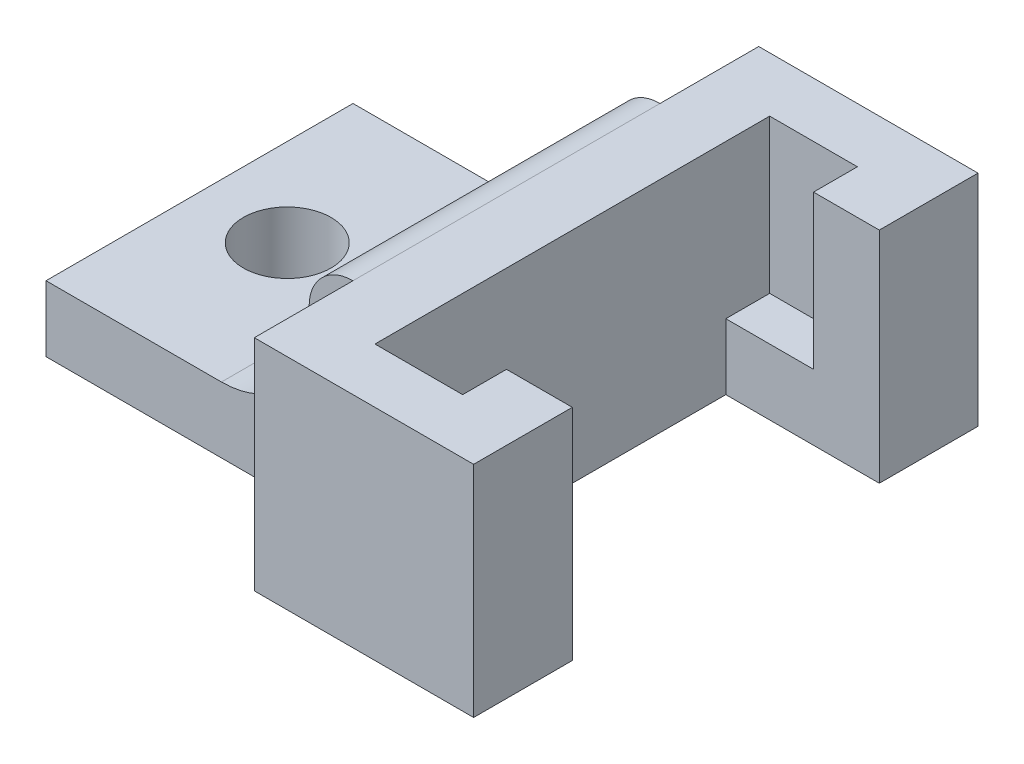
SolidWorks part; units mm, degrees
ref_plane "Front Plane" through (0, 0, 0) normal (0, 0, 1) x (1, 0, 0)
ref_plane "Top Plane" through (0, 0, 0) normal (0, 1, 0) x (1, 0, 0)
ref_plane "Right Plane" through (0, 0, 0) normal (1, 0, 0) x (0, 0, -1)
sketch "Sketch1" plane through (0, 0, 0) normal (0, 1, 0) x (1, 0, 0)
  line L0 (0, 7) -> (14, 7) construction
  line L1 (0, 0) -> (14, 0)
  line L2 (0, 0) -> (0, 14)
  line L3 (0, 14) -> (14, 14)
  line L4 (14, 0) -> (14, 14)
  line L6 (14, 18.5) -> (24, 18.5)
  line L7 (14, 18.5) -> (14, -4.5)
  line L8 (14, -4.5) -> (24, -4.5)
  line L9 (24, 18.5) -> (24, -4.5)
  line L10 (14, 18.5) -> (24, -4.5) construction
  line L11 (14, -4.5) -> (24, 18.5) construction
  line L12 (17, 14) -> (24, 14)
  line L13 (17, 14) -> (17, 0)
  line L14 (17, 0) -> (24, 0)
  line L15 (24, 14) -> (24, 0)
  line L16 (17, 14) -> (24, 0) construction
  line L17 (17, 0) -> (24, 14) construction
  line L18 (17, 16) -> (21, 16) construction
  line L19 (17, 16) -> (17, -2) construction
  line L20 (17, -2) -> (21, -2) construction
  line L21 (21, 16) -> (21, -2) construction
  line L22 (17, 16) -> (21, -2) construction
  line L23 (17, -2) -> (21, 16) construction
  circle A0 centre (4, 7) radius 2
  point P9 (19, 7)
  point P14 (19, 7)
  point P15 (20.5, 7)
  dimension "D2" = 4
  dimension "D1" = 14
  dimension "D3" = 4
  dimension "D4" = 10
  dimension "D5" = 23
  dimension "D6" = 10
  dimension "D7" = 14
  dimension "D8" = 4
  dimension "D9" = 18
extrude "Boss-Extrude1" add sketch "Sketch1" along normal blind 10 contours L14 L13 L12 L9 L6 L7 L4 L8 | L1 L4 L3 L2 A0
sketch "Sketch3" plane through (0, 10, 0) normal (0, 1, 0) x (1, 0, 0)
  line L0 (17, 14) -> (17, 0) construction
  line L1 (17, 16) -> (21, 16)
  line L2 (17, 16) -> (17, -2)
  line L3 (17, -2) -> (21, -2)
  line L4 (21, 16) -> (21, -2)
  line L5 (17, 16) -> (21, -2) construction
  line L6 (17, -2) -> (21, 16) construction
  line L7 (0, 0) -> (14, 0) construction
  line L8 (0, 14) -> (12, 14)
  line L9 (0, 14) -> (0, 0)
  line L10 (0, 0) -> (12, 0)
  line L11 (12, 14) -> (12, 0)
  point P0 (19, 7)
  point P14 (0, 0)
  point P15 (12, 7)
  dimension "D2" = 18
  dimension "D3" = 4
  dimension "D1" = 12
extrude "Cut-Extrude1" cut sketch "Sketch3" against normal blind 7
fillet "Fillet1" radius 4 1 edges at (12, 3, -7)
fillet "Fillet2" radius 2 1 edges at (12, 10, -7)
sketch "Sketch4" plane through (0, 0, 0) normal (0, -1, 0) x (1, 0, 0)
  line L1 (7.05, -2.5) -> (9.05, -2.5)
  line L2 (7.05, -2.5) -> (7.05, -11.5)
  line L3 (7.05, -11.5) -> (9.05, -11.5)
  line L4 (9.05, -2.5) -> (9.05, -11.5)
  line L5 (7.05, -2.5) -> (9.05, -11.5) construction
  line L6 (7.05, -11.5) -> (9.05, -2.5) construction
  circle A2 centre (4, -7) radius 2
  circle A3 centre (4, -7) radius 2 construction
  point P0 (8.05, -7)
  point P8 (0, 0)
  dimension "D2" = 3.05
  dimension "D3" = 9
  dimension "D4" = 2
  dimension "D1" = 0
extrude "Boss-Extrude2" add sketch "Sketch4" along normal blind 4
fillet "Fillet3" radius 2 1 edges at (9.05, 0, -7)
